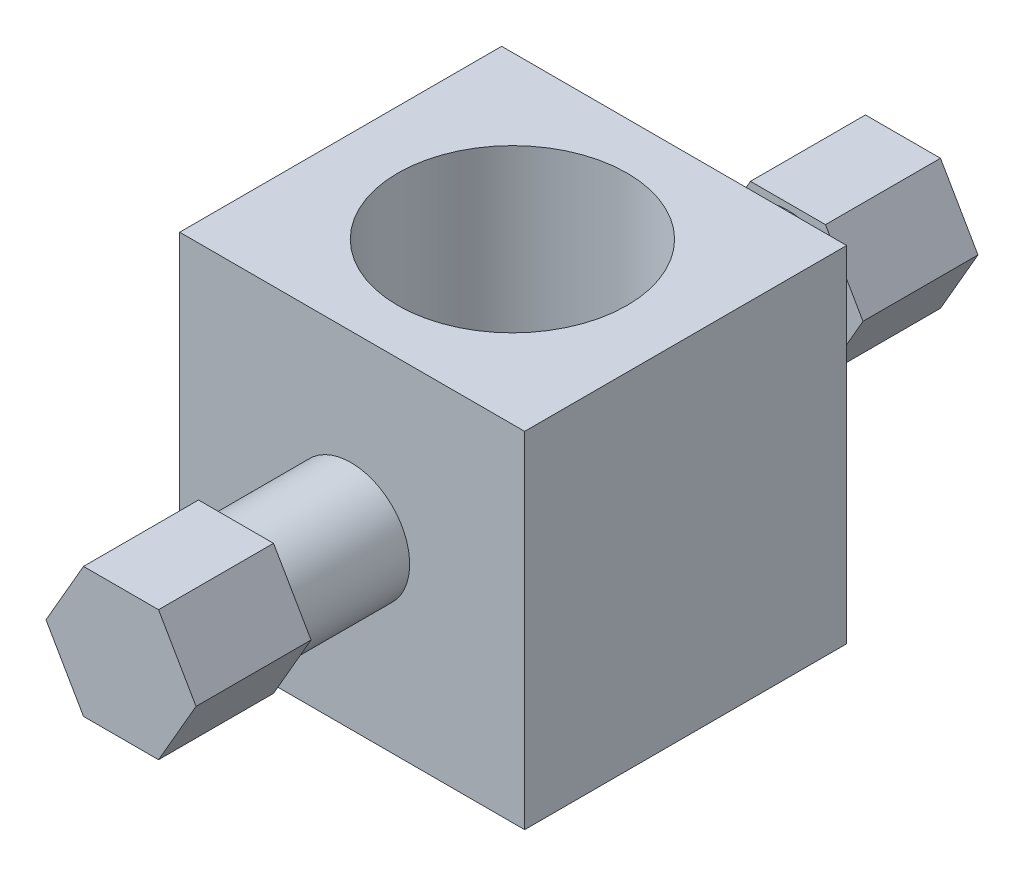
SolidWorks part; units mm, degrees
ref_plane "Front Plane" through (0, 0, 0) normal (0, 0, 1) x (1, 0, 0)
ref_plane "Top Plane" through (0, 0, 0) normal (0, 1, 0) x (1, 0, 0)
ref_plane "Right Plane" through (0, 0, 0) normal (1, 0, 0) x (0, 0, -1)
sketch "Sketch1" plane through (0, 0, 0) normal (0, 0, 1) x (1, 0, 0)
  circle A0 centre (0, 0) radius 2.55
  dimension "D1" = 5.1
extrude "Boss-Extrude1" add sketch "Sketch1" along normal blind 24
sketch "Sketch2" plane through (0, 0, 24) normal (0, 0, 1) x (1, 0, 0)
  line L1 (3.2622, 0) -> (1.6311, 2.8251)
  line L2 (1.6311, 2.8251) -> (-1.6311, 2.8251)
  line L3 (-1.6311, 2.8251) -> (-3.2622, 0)
  line L4 (-3.2622, 0) -> (-1.6311, -2.8251)
  line L5 (-1.6311, -2.8251) -> (1.6311, -2.8251)
  line L6 (1.6311, -2.8251) -> (3.2622, 0)
  circle A0 centre (0, 0) radius 2.8251 construction
extrude "Boss-Extrude2" add sketch "Sketch2" along normal blind 5
sketch "Sketch3" plane through (0, 0, 0) normal (0, 0, -1) x (-1, 0, 0)
  line L1 (3.2622, 0) -> (1.6311, 2.8251)
  line L2 (1.6311, 2.8251) -> (-1.6311, 2.8251)
  line L3 (-1.6311, 2.8251) -> (-3.2622, 0)
  line L4 (-3.2622, 0) -> (-1.6311, -2.8251)
  line L5 (-1.6311, -2.8251) -> (1.6311, -2.8251)
  line L6 (1.6311, -2.8251) -> (3.2622, 0)
  circle A0 centre (0, 0) radius 2.8251 construction
extrude "Boss-Extrude3" add sketch "Sketch3" along normal blind 5
sketch "Sketch4" plane through (0, 0, 0) normal (0, 1, 0) x (1, 0, 0)
  line L0 (2.55, -24) -> (2.55, 0) construction
  line L1 (-7.45, -5) -> (7.55, -5)
  line L2 (-7.45, -5) -> (-7.45, -19)
  line L3 (-7.45, -19) -> (7.55, -19)
  line L4 (7.55, -5) -> (7.55, -19)
  line L6 (-2.55, 0) -> (-2.55, -24) construction
  line L7 (-2.55, 0) -> (2.55, 0) construction
  dimension "D1" = 15
  dimension "D2" = 14
  dimension "D3" = 5
  dimension "D4" = 4.9
  dimension "D5" = 5
extrude "Boss-Extrude5" add sketch "Sketch4" against normal blind 7.5 and the other way blind 7.5
sketch "Sketch9" plane through (0, 7.5, 0) normal (0, 1, 0) x (1, 0, 0)
  circle A0 centre (0.05, -12.0314) radius 4.9864
  point P3 (0.05, -5)
  point P4 (0.05, -5)
  dimension "D1" = 9.9727
extrude "Cut-Extrude2" cut sketch "Sketch9" against normal blind 16.5
